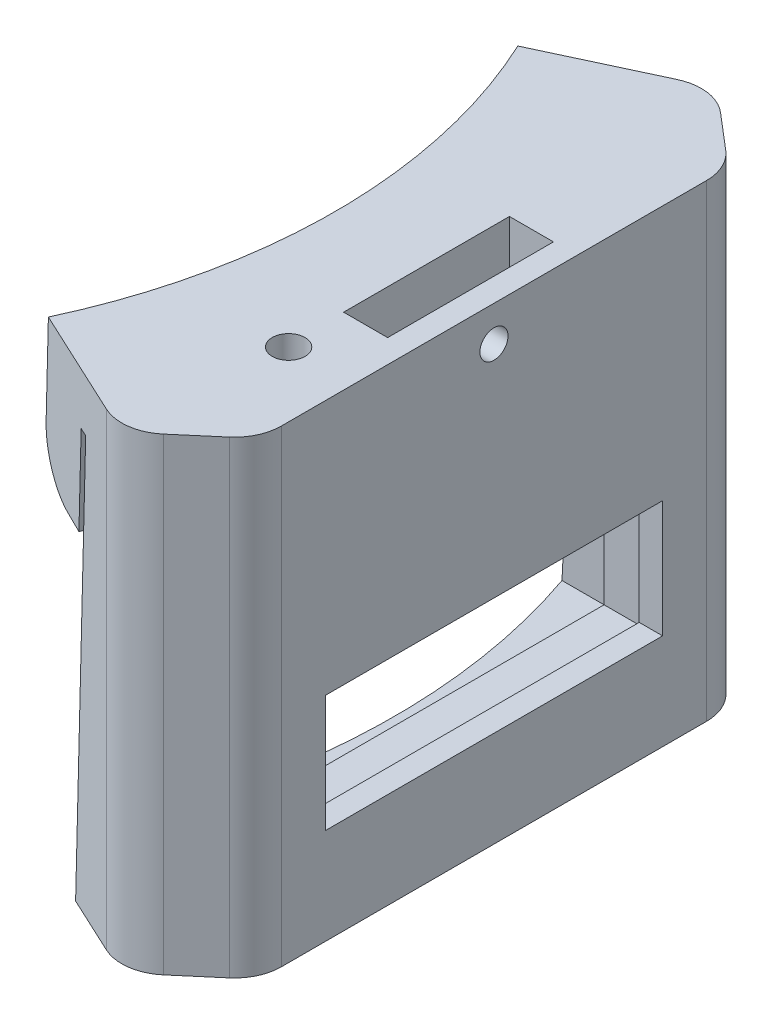
SolidWorks part; units mm, degrees
ref_plane "Plano frontal" through (0, 0, 0) normal (0, 0, 1) x (1, 0, 0)
ref_plane "Plano superior" through (0, 0, 0) normal (0, 1, 0) x (1, 0, 0)
ref_plane "Plano direito" through (0, 0, 0) normal (1, 0, 0) x (0, 0, -1)
sketch "Esboço1" plane through (0, 0, 0) normal (0, 0, 1) x (1, 0, 0)
  line L0 (0, 0) -> (135, 0) construction
  line L1 (135, 0) -> (125, -200) construction
  line L2 (125, -200) -> (0, -200) construction
  line L3 (0, -200) -> (0, 0) construction
  line L4 (133.0475, 1) -> (132.0619, -18.7116)
  line L5 (132.0619, -18.7116) -> (117.0806, -17.9626)
  line L6 (117.0806, -17.9626) -> (118.5788, 12)
  line L7 (118.5788, 12) -> (150.6, 12)
  line L8 (150.6, 12) -> (150.6, -88)
  line L9 (150.6, -88) -> (130.6, -88)
  line L10 (130.6, -88) -> (135.05, 1)
  line L11 (135.05, 1) -> (133.0475, 1)
  dimension "D1" = 135
  dimension "D2" = 125
  dimension "D3" = 200
  dimension "D4" = 30
  dimension "D5" = 100
  dimension "D6" = 2
  dimension "D7" = 15
  dimension "D8" = 20
  dimension "D9" = 11
  dimension "D10" = 1
revolve "Revolução2" add sketch "Esboço1" angle 50 mid plane about L3
sketch "Esboço9" plane through (0, 0, 0) normal (1, 0, 0) x (0, 0, -1)
  line L0 (0, -200) -> (0, 0) construction
  line L1 (-41, -73) -> (41, -73)
  line L2 (-41, -73) -> (-41, -37)
  line L3 (-41, -37) -> (41, -37)
  line L4 (41, -73) -> (41, -37)
  line L5 (-41, -73) -> (41, -37) construction
  line L6 (-41, -37) -> (41, -73) construction
  line L7 (-63.6463, -88) -> (63.6463, -88) construction
  point P0 (0, -55)
  dimension "D1" = 82
  dimension "D2" = 36
  dimension "D3" = 15
sketch "Esboço10" plane through (0, 12, 0) normal (0, 1, 0) x (1, 0, 0)
  line L0 (136.49, 63.6463) -> (136.49, -63.6463)
  line L2 (152.49, -50) -> (152.49, 50)
  line L4 (136.49, 63.6463) -> (152.49, 50)
  line L5 (152.49, 50) -> (152.49, -50)
  line L6 (152.49, -50) -> (136.49, -63.6463)
  line L7 (0, 0) -> (178.1379, 0) construction
  point P6 (152.49, 0)
  arc M1 (136.49, -63.6463) -> (136.49, 63.6463) centre (0, 0) ccw
  dimension "D1" = 100
  dimension "D2" = 16
sketch "Esboço11" plane through (0, 0, 0) normal (1, 0, 0) x (0, 0, -1)
  line L0 (0, -200) -> (0, 0) construction
  line L1 (-36, -67.5) -> (36, -67.5)
  line L2 (-36, -67.5) -> (-36, -42.5)
  line L3 (-36, -42.5) -> (36, -42.5)
  line L4 (36, -67.5) -> (36, -42.5)
  line L5 (-36, -67.5) -> (36, -42.5) construction
  line L6 (-36, -42.5) -> (36, -67.5) construction
  line L12 (-41, -73) -> (41, -73)
  line L13 (41, -73) -> (41, -37)
  line L14 (41, -37) -> (-41, -37)
  line L15 (-41, -37) -> (-41, -73)
  line L16 (-41, -73) -> (41, -73) construction
  line L17 (41, -73) -> (41, -37) construction
  line L18 (41, -37) -> (-41, -37) construction
  line L19 (-41, -37) -> (-41, -73) construction
  point P0 (0, -55)
  point P7 (41, -55)
  point P11 (36, -55)
  dimension "D1" = 72
  dimension "D2" = 25
  dimension "D4" = 0
extrude "Ressalto-extrusão1" add sketch "Esboço10" against normal up to surface (100 mm away) contours L7 L6 L2 M1 | L7 L5 L4 M1 up to face at (134.0134, -88, 0)
extrude "Corte-extrusão6" cut sketch "Esboço9" along normal blind 147.5
extrude "Corte-extrusão7" cut sketch "Esboço11" along normal blind 172
sketch "Esboço15" plane through (0, 12, 0) normal (0, 1, 0) x (1, 0, 0)
  line L0 (152.49, -50) -> (152.49, 50) construction
  line L1 (152.49, 0) -> (118.4745, 0) construction
  line L2 (132.0619, 0) -> (117.0806, 0) construction
  circle A0 centre (138.65, -30) radius 3.5
  dimension "D1" = 7
  dimension "D2" = 13.84
  dimension "D3" = 30
extrude "Corte-extrusão8" cut sketch "Esboço15" against normal up to surface (49 mm away) up to face at (138.7076, -37, 0)
sketch "Esboço16" plane through (0, 0, 0) normal (1, 0, 0) x (0, 0, -1)
  line L0 (-41, -37) -> (41, -37) construction
  line L1 (-41, -37) -> (41, -37)
  line L2 (-41, -73) -> (-41, -37) construction
  line L3 (41, -73) -> (-41, -73) construction
  line L4 (41, -37) -> (41, -73) construction
  line L5 (-41, -73) -> (-41, -37)
  line L6 (41, -73) -> (-41, -73)
  line L7 (41, -37) -> (41, -73)
  line L8 (43, -35) -> (43, -75)
  line L9 (43, -75) -> (-43, -75)
  line L10 (-43, -75) -> (-43, -35)
  line L11 (-43, -35) -> (43, -35)
  dimension "D1" = 2
extrude "Corte-extrusão9" cut sketch "Esboço16" along normal blind 135
sketch "Esboço17" plane through (0, 12, 0) normal (0, 1, 0) x (1, 0, 0)
  line L0 (150.6, 0) -> (130.6, 0) construction
  line L1 (138.09, -17.7) -> (147.49, -17.7)
  line L2 (138.09, -17.7) -> (138.09, 17.7)
  line L3 (138.09, 17.7) -> (147.49, 17.7)
  line L4 (147.49, -17.7) -> (147.49, 17.7)
  line L5 (138.09, -17.7) -> (147.49, 17.7) construction
  line L6 (138.09, 17.7) -> (147.49, -17.7) construction
  line L7 (152.49, -50) -> (152.49, 50) construction
  point P0 (142.79, 0)
  dimension "D1" = 35.4
  dimension "D2" = 9.4
  dimension "D3" = 5
extrude "Corte-extrusão10" cut sketch "Esboço17" against normal blind 30
sketch "Esboço18" plane through (152.49, 0, 0) normal (1, 0, 0) x (0, 0, -1)
  line L0 (0, -17.9626) -> (0, 12) construction
  circle A0 centre (0, 4.4652) radius 3
  dimension "D1" = 6
extrude "Corte-extrusão12" cut sketch "Esboço18" against normal up to surface (5 mm away) up to face at (147.49, -3, 0)
fillet "Filete1" radius 10 5 edges at (117.0806, -17.9626, 0) (152.49, -38, 50) (152.49, -38, -50) (136.49, -38, -63.6463) (136.49, -38, 63.6463)
